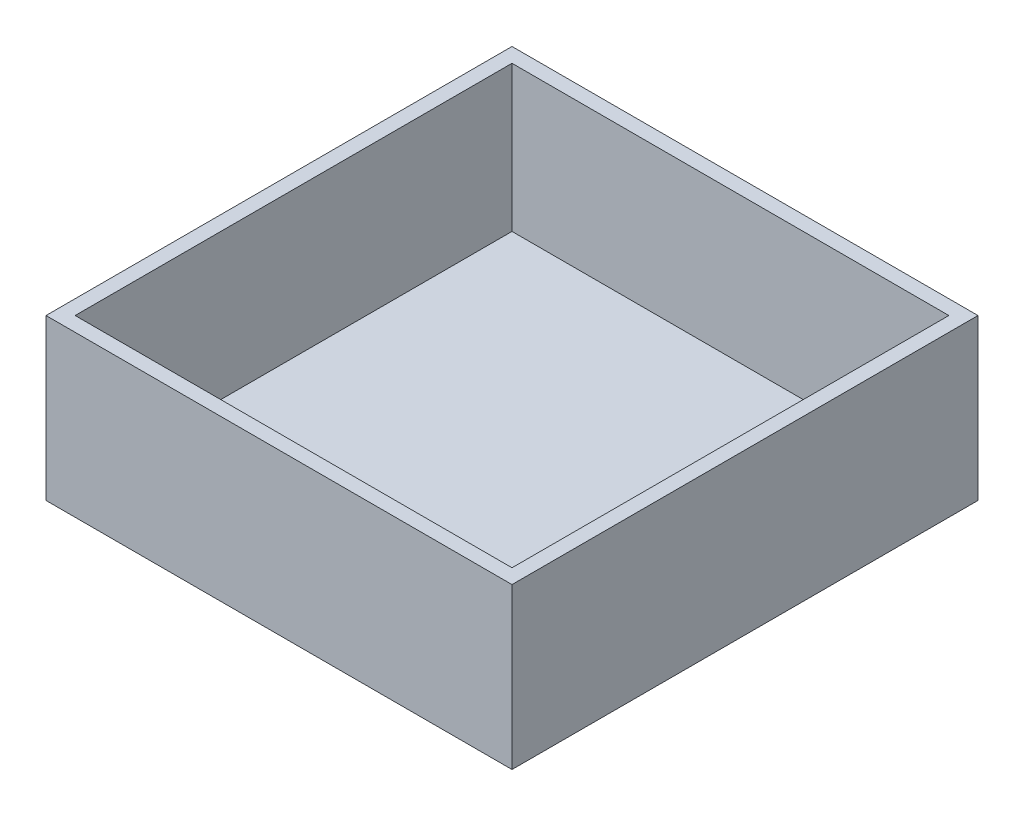
SolidWorks part; units mm, degrees
material "ABS"
ref_plane "Plan de face" through (0, 0, 0) normal (0, 0, 1) x (1, 0, 0)
ref_plane "Plan de dessus" through (0, 0, 0) normal (0, 1, 0) x (1, 0, 0)
ref_plane "Plan de droite" through (0, 0, 0) normal (1, 0, 0) x (0, 0, -1)
sketch "Esquisse1" plane through (0, 0, 0) normal (0, 1, 0) x (1, 0, 0)
  line L1 (-75, -75) -> (75, -75)
  line L2 (-75, -75) -> (-75, 75)
  line L3 (-75, 75) -> (75, 75)
  line L4 (75, -75) -> (75, 75)
  point P4 (0, -75)
  point P7 (-75, 0)
  dimension "D3" = 150
  dimension "D4" = 150
extrude "Boss.-Extru.1" add sketch "Esquisse1" along normal blind 50
shell "Coque1" thickness 5
